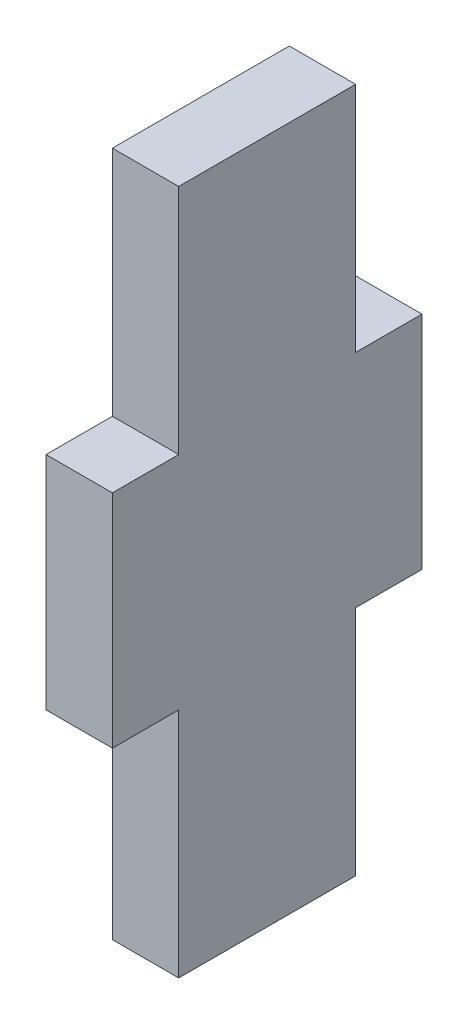
SolidWorks part; units mm, degrees
ref_plane "Plan de face" through (0, 0, 0) normal (0, 0, 1) x (1, 0, 0)
ref_plane "Plan de dessus" through (0, 0, 0) normal (0, 1, 0) x (1, 0, 0)
ref_plane "Plan de droite" through (0, 0, 0) normal (1, 0, 0) x (0, 0, -1)
sketch "Esquisse1" plane through (-97.0031, 0, 0) normal (-1, 0, 0) x (0, 0, 1)
  line L0 (206, -2.7042) -> (125.2307, -2.7042) construction
  line L1 (192, -33.7042) -> (192, 65.7737) construction
  line L2 (184, -12.7042) -> (178, -12.7042)
  line L3 (184, 7.2958) -> (184, -12.7042)
  line L4 (200, 28.2958) -> (184, 28.2958)
  line L5 (184, 28.2958) -> (184, 22.2958)
  line L6 (184, 22.2958) -> (200, 22.2958)
  line L7 (200, 22.2958) -> (200, 28.2958)
  line L8 (200, 28.2958) -> (184, 28.2958)
  line L9 (184, 28.2958) -> (184, 22.2958)
  line L10 (184, 22.2958) -> (200, 22.2958)
  line L11 (200, 22.2958) -> (200, 28.2958)
  line L12 (200, -12.7042) -> (206, -12.7042)
  line L13 (206, -12.7042) -> (206, 7.2958)
  line L14 (206, 7.2958) -> (200, 7.2958)
  line L15 (200, 7.2958) -> (200, -12.7042)
  line L16 (200, -12.7042) -> (206, -12.7042)
  line L17 (206, -12.7042) -> (206, 7.2958)
  line L18 (206, 7.2958) -> (200, 7.2958)
  line L19 (200, 7.2958) -> (200, -12.7042)
  line L20 (200, -27.7042) -> (184, -27.7042)
  line L21 (184, -27.7042) -> (184, -33.7042)
  line L22 (184, -33.7042) -> (200, -33.7042)
  line L23 (200, -33.7042) -> (200, -27.7042)
  line L24 (200, -27.7042) -> (184, -27.7042)
  line L25 (184, -27.7042) -> (184, -33.7042)
  line L26 (184, -33.7042) -> (200, -33.7042)
  line L27 (200, -33.7042) -> (200, -27.7042)
  line L28 (178, 7.2958) -> (184, 7.2958)
  line L29 (178, -12.7042) -> (178, 7.2958)
  dimension "D1" = 0
  dimension "D2" = 0
  dimension "D3" = 0
extrude "Boss.-Extru.2" add sketch "Esquisse1" along normal blind 6
sketch "Esquisse2" plane through (0, 0, 200) normal (0, 0, -1) x (-1, 0, 0)
  line L0 (12.0031, 22.2958) -> (103.0031, 22.2958) construction
  line L1 (103.0031, 22.2958) -> (103.0031, 7.2958) construction
  line L2 (103.0031, -12.7042) -> (103.0031, -27.7042) construction
  line L3 (103.0031, -27.7042) -> (12.0031, -27.7042) construction
  line L4 (12.0031, 22.2958) -> (103.0031, 22.2958)
  line L5 (103.0031, 22.2958) -> (103.0031, 7.2958)
  line L6 (103.0031, -12.7042) -> (103.0031, -27.7042)
  line L7 (103.0031, -27.7042) -> (12.0031, -27.7042)
  line L8 (97.0031, 7.2958) -> (97.0031, -12.7042) construction
  line L9 (97.0031, 7.2958) -> (97.0031, -12.7042)
  line L10 (103.0031, 7.2958) -> (103.0031, -27.7042)
  line L11 (97.0031, -12.7042) -> (97.0031, -27.7042)
  line L12 (97.0031, 7.2958) -> (97.0031, 22.2958)
extrude "Boss.-Extru.3" add sketch "Esquisse2" along normal up to surface (16 mm away) contours L12 L9 L11 L7 L6 L10 L5 L4 up to face at (-100.0031, -2.7042, 184)
